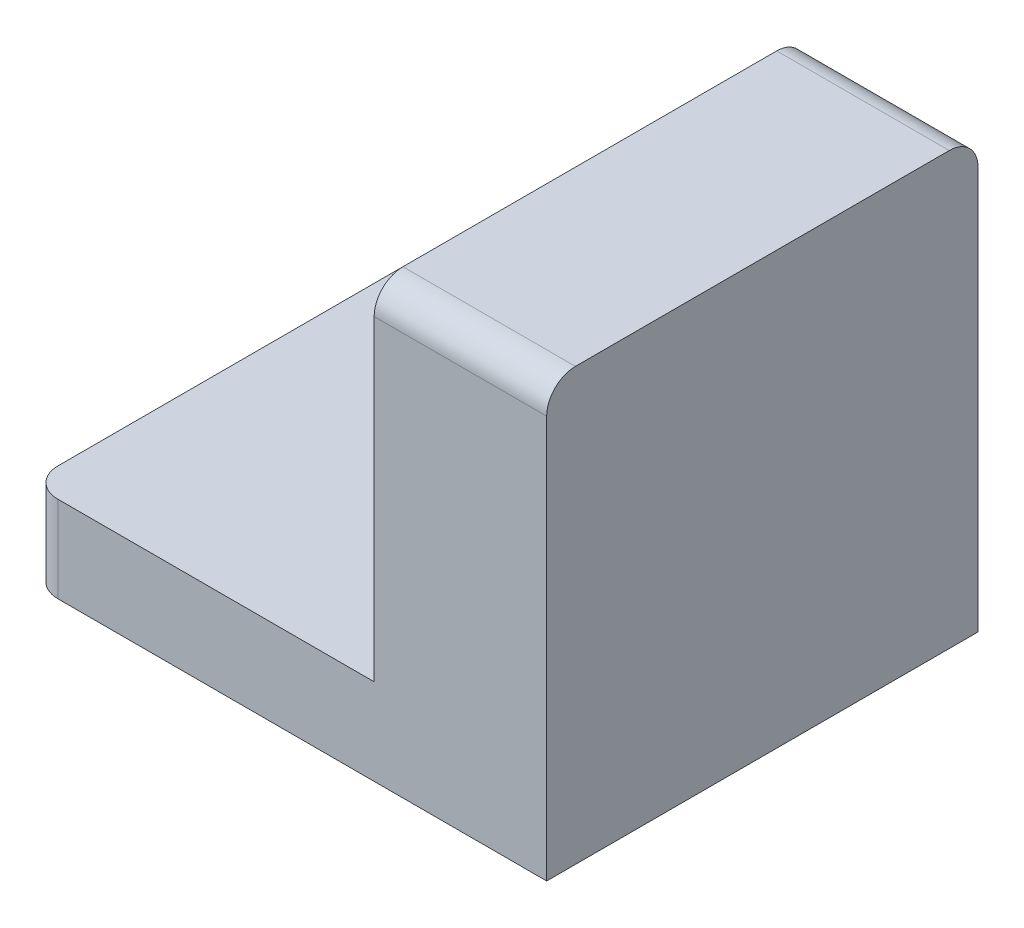
SolidWorks part; units mm, degrees
ref_plane "前基準面" through (0, 0, 0) normal (0, 0, 1) x (1, 0, 0)
ref_plane "上基準面" through (0, 0, 0) normal (0, 1, 0) x (1, 0, 0)
ref_plane "右基準面" through (0, 0, 0) normal (1, 0, 0) x (0, 0, -1)
sketch "草圖1" plane through (0, 0, 0) normal (0, 1, 0) x (1, 0, 0)
  line L1 (10, -7.5) -> (-8, -7.5)
  line L2 (10, -7.5) -> (10, 7.5)
  line L3 (10, 7.5) -> (-8, 7.5)
  line L4 (-8, -7.5) -> (-8, 7.5)
  line L5 (0, -55) -> (0, 55) construction
  line L6 (-55, 0) -> (55, 0) construction
  point P0 (0, 0)
  dimension "D1" = 8
  dimension "D2" = 15
  dimension "D3" = 10
  dimension "D4" = 7.5
extrude "填料-伸長1" add sketch "草圖1" along normal blind 15
sketch "草圖2" plane through (0, 15, 0) normal (0, 1, 0) x (1, 0, 0)
  line L0 (-8, -7.5) -> (10, -7.5) construction
  line L1 (-8, 7.5) -> (4, 7.5)
  line L2 (-8, 7.5) -> (-8, -7.5)
  line L3 (-8, -7.5) -> (4, -7.5)
  line L4 (4, 7.5) -> (4, -7.5)
  line L5 (10, -7.5) -> (10, 7.5) construction
  dimension "D1" = 6
extrude "除料-伸長1" cut sketch "草圖2" against normal blind 12
fillet "圓角1" radius 1 4 edges at (-8, 1.5, 7.5) (-8, 1.5, -7.5) (7, 15, -7.5) (7, 15, 7.5)
sketch "草圖3" plane through (4, 0, 0) normal (-1, 0, 0) x (0, 0, 1)
  line L0 (0, -8.25) -> (0, 8.25) construction
  line L3 (8.25, 0) -> (-8.25, 0) construction
  circle A0 centre (0, 9) radius 5.125
  dimension "D1" = 10.25
  dimension "D2" = 9
extrude "除料-伸長2" cut sketch "草圖3" against normal blind 5.5
sketch "草圖4" plane through (0, 3, 0) normal (0, 1, 0) x (1, 0, 0)
  circle A0 centre (0, 0) radius 2.125
  dimension "D1" = 4.25
extrude "除料-伸長3" cut sketch "草圖4" against normal blind 5.5
